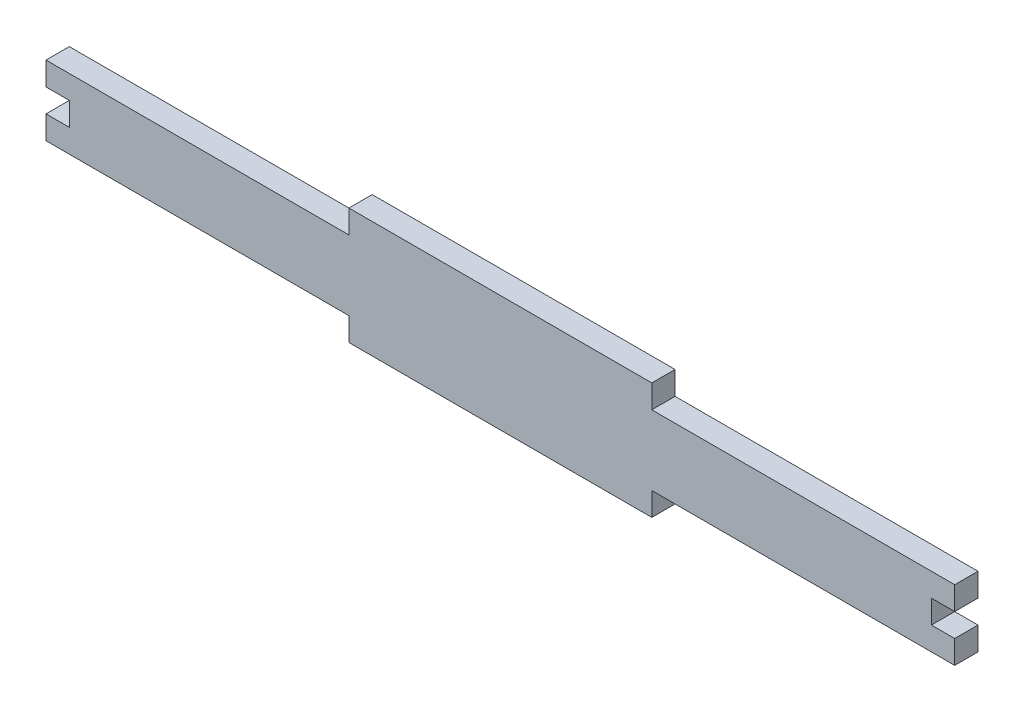
SolidWorks part; units mm, degrees
ref_plane "Front Plane" through (0, 0, 0) normal (0, 0, 1) x (1, 0, 0)
ref_plane "Top Plane" through (0, 0, 0) normal (0, 1, 0) x (1, 0, 0)
ref_plane "Right Plane" through (0, 0, 0) normal (1, 0, 0) x (0, 0, -1)
sketch "Sketch1" plane through (0, 0, 0) normal (0, 0, 1) x (1, 0, 0)
  line L1 (-58.5, -7.5) -> (58.5, -7.5) construction
  line L2 (-58.5, -7.5) -> (-58.5, 7.5) construction
  line L3 (-58.5, 7.5) -> (58.5, 7.5) construction
  line L4 (58.5, -7.5) -> (58.5, 7.5) construction
  line L5 (-58.5, -7.5) -> (58.5, 7.5) construction
  line L6 (-58.5, 7.5) -> (58.5, -7.5) construction
  line L11 (-46.4777, -5.9587) -> (46.4777, 5.9587) construction
  line L12 (-46.4777, 5.9587) -> (46.4777, -5.9587) construction
  line L14 (-19.5, -7.5) -> (19.5, -7.5)
  line L18 (58.5, -1.5) -> (55.5, -1.5)
  line L19 (55.5, -1.5) -> (55.5, 1.5)
  line L20 (55.5, 1.5) -> (58.5, 1.5)
  line L24 (19.5, 7.5) -> (-19.5, 7.5)
  line L28 (-58.5, 1.5) -> (-55.5, 1.5)
  line L29 (-55.5, 1.5) -> (-55.5, -1.5)
  line L30 (-55.5, -1.5) -> (-58.5, -1.5)
  line L32 (-19.5, -7.5) -> (-19.5, -4.5)
  line L33 (-19.5, -4.5) -> (-58.5, -4.5)
  line L34 (-19.5, 7.5) -> (-19.5, 4.5)
  line L35 (-19.5, 4.5) -> (-58.5, 4.5)
  line L36 (-58.5, 4.5) -> (-58.5, 1.5)
  line L37 (-58.5, -1.5) -> (-58.5, -4.5)
  line L38 (19.5, 7.5) -> (19.5, 4.5)
  line L39 (19.5, 4.5) -> (58.5, 4.5)
  line L40 (58.5, 4.5) -> (58.5, 1.5)
  line L41 (58.5, -1.5) -> (58.5, -4.5)
  line L42 (58.5, -4.5) -> (19.5, -4.5)
  line L43 (19.5, -4.5) -> (19.5, -7.5)
  point P0 (0, 0)
  point P6 (0, 0)
  point P32 (58.5, 2.7684)
  dimension "D1" = 117
  dimension "D2" = 15
  dimension "D3" = 3
extrude "Boss-Extrude1" add sketch "Sketch1" along normal blind 3
